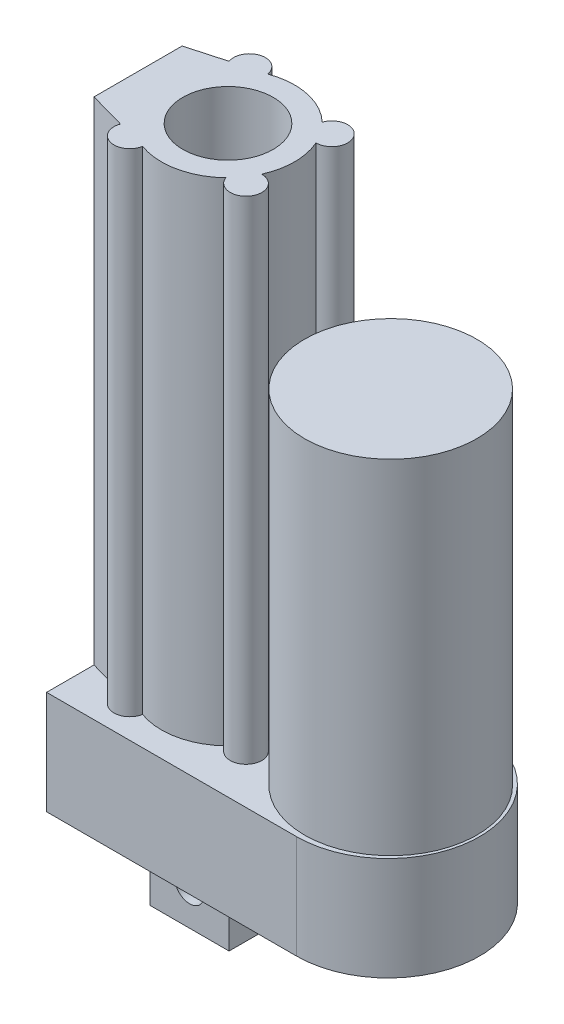
SolidWorks part; units mm, degrees
ref_plane "Front Plane" through (0, 0, 0) normal (0, 0, 1) x (1, 0, 0)
ref_plane "Top Plane" through (0, 0, 0) normal (0, 1, 0) x (1, 0, 0)
ref_plane "Right Plane" through (0, 0, 0) normal (1, 0, 0) x (0, 0, -1)
sketch "Sketch1" plane through (0, 0, 0) normal (0, 1, 0) x (1, 0, 0)
  line L0 (13.4907, 9.5) -> (13.4907, -9.5) construction
  line L1 (-8.4917, 13.25) -> (-8.4917, -13.25) construction
  line L2 (-3.971, 14.2054) -> (-19.9093, 9.75)
  line L3 (-19.9093, 9.75) -> (-19.9093, -9.75)
  line L4 (-19.9093, -9.75) -> (-3.971, -14.2054)
  circle A0 centre (0, 0) radius 14.75
  circle A1 centre (-8.4917, -13.25) radius 3.5
  circle A2 centre (-8.4917, 13.25) radius 3.5
  circle A3 centre (13.4907, 9.5) radius 3.5
  circle A4 centre (13.4907, -9.5) radius 3.5
  circle A5 centre (0, 0) radius 10
  point P11 (-8.4917, 0)
  point P13 (-19.9093, 0)
  point P14 (13.4907, 0)
  dimension "D1" = 29.5
  dimension "D2" = 7
  dimension "D3" = 33.5
  dimension "D4" = 26
  dimension "D5" = 20
  dimension "D6" = 29.3
  dimension "D7" = 30
  dimension "D8" = 36.9
  dimension "D9" = 19.5
extrude "Boss-Extrude1" add sketch "Sketch1" along normal blind 108.9 contours A2 L2 L3 L4 A1 A0 | L4 A1 A0 | L4 A1 | A0 A1 | A4 A0 A3 A2 A1 A5 | A5 | L2 A2 | A0 A2 | A0 A2 L2 | A0 A3 | A0 A4 | A0 A4 | A0 A3
sketch "Sketch2" plane through (0, 0, 0) normal (0, 1, 0) x (1, 0, 0)
  line L0 (-19.9093, 9.75) -> (-19.9093, -9.75) construction
  circle A0 centre (36.0157, 0) radius 19.075
  dimension "D1" = 38.15
  dimension "D2" = 75
extrude "Boss-Extrude2" add sketch "Sketch2" along normal blind 76 separate body
sketch "Sketch3" plane through (0, 0, 0) normal (0, 1, 0) x (1, 0, 0)
  line L0 (-19.9093, 20.25) -> (-19.9093, -20.25)
  line L1 (-19.9093, -20.25) -> (35.4407, -20.25)
  line L2 (35.4407, 20.25) -> (-19.9093, 20.25)
  line L3 (-19.9093, 9.75) -> (-19.9093, -9.75) construction
  arc A0 (35.4407, -20.25) -> (35.4407, 20.25) centre (35.4407, 0) ccw
  point P7 (-19.9093, 0)
  point P9 (0, 0)
  dimension "D2" = 75.6
  dimension "D1" = 40.5
extrude "Boss-Extrude3" add sketch "Sketch3" against normal blind 22.9
sketch "Sketch4" plane through (0, -22.9, 0) normal (0, -1, 0) x (1, 0, 0)
  line L1 (-8.5093, 8.75) -> (8.9907, 8.75)
  line L2 (-8.5093, 8.75) -> (-8.5093, -8.75)
  line L3 (-8.5093, -8.75) -> (8.9907, -8.75)
  line L4 (8.9907, 8.75) -> (8.9907, -8.75)
  line L6 (-19.9093, -20.25) -> (-19.9093, 20.25) construction
  point P6 (8.9907, 0)
  dimension "D1" = 17.5
  dimension "D2" = 17.5
  dimension "D3" = 11.4
extrude "Boss-Extrude4" add sketch "Sketch4" along normal blind 18
sketch "Sketch5" plane through (0, 0, -8.75) normal (0, 0, -1) x (-1, 0, 0)
  line L0 (8.5093, -40.9) -> (-8.9907, -40.9) construction
  line L1 (-8.9907, -32.95) -> (8.5093, -32.95) construction
  line L2 (-8.9907, -40.9) -> (-8.9907, -22.9) construction
  line L3 (8.5093, -40.9) -> (8.5093, -22.9) construction
  circle A0 centre (-0.2407, -32.95) radius 3.25
  point P10 (-0.2407, -32.95)
  dimension "D1" = 6.5
  dimension "D2" = 4.7
extrude "Cut-Extrude1" cut sketch "Sketch5" against normal up to surface (17.5 mm away) up to face at (0.2407, -31.9, 8.75)
sketch "Sketch6" plane through (0, 108.9, 0) normal (0, 1, 0) x (1, 0, 0)
  circle A0 centre (0, 0) radius 10
  dimension "D1" = 20
extrude "Cut-Extrude2" cut sketch "Sketch6" against normal blind 79
